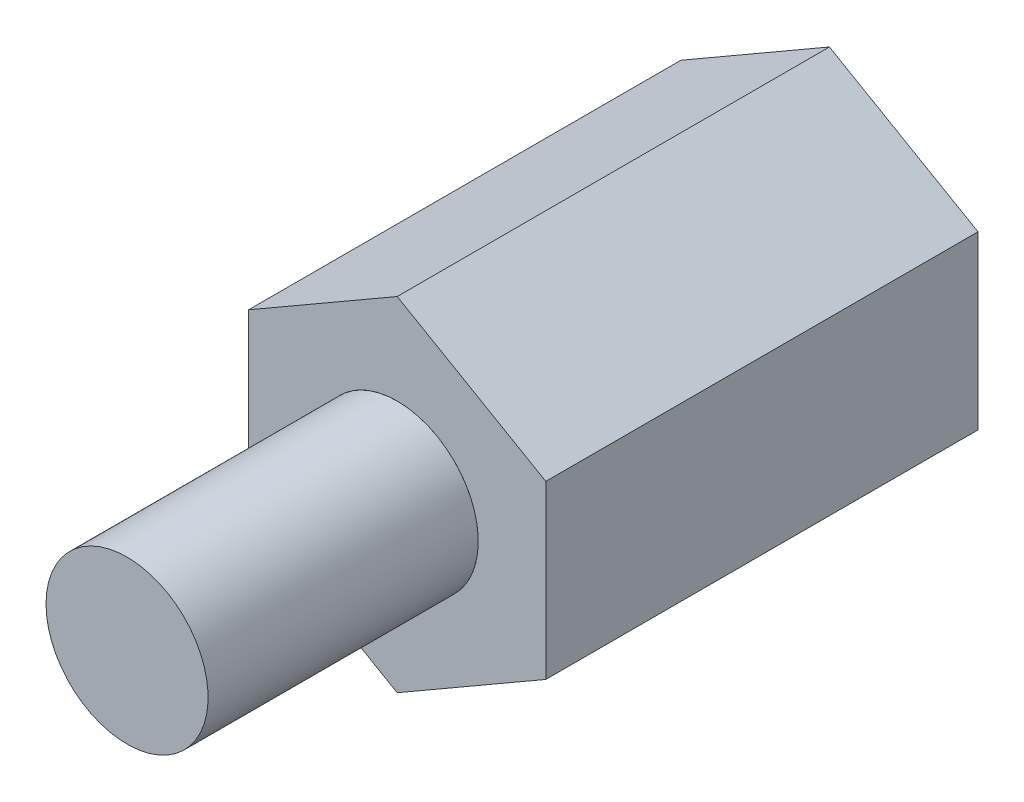
SolidWorks part; units mm, degrees
ref_plane "Спереди" through (0, 0, 0) normal (0, 0, 1) x (1, 0, 0)
ref_plane "Сверху" through (0, 0, 0) normal (0, 1, 0) x (1, 0, 0)
ref_plane "Справа" through (0, 0, 0) normal (1, 0, 0) x (0, 0, -1)
sketch "Эскиз1" plane through (0, 0, 0) normal (0, 0, 1) x (1, 0, 0)
  line L1 (2.75, 1.5877) -> (0, 3.1754)
  line L2 (0, 3.1754) -> (-2.75, 1.5877)
  line L3 (-2.75, 1.5877) -> (-2.75, -1.5877)
  line L4 (-2.75, -1.5877) -> (0, -3.1754)
  line L5 (0, -3.1754) -> (2.75, -1.5877)
  line L6 (2.75, -1.5877) -> (2.75, 1.5877)
  circle A0 centre (0, 0) radius 2.75 construction
  circle A1 centre (0, 0) radius 1.5
  dimension "D2" = 3
  dimension "D1" = 5.5
extrude "Бобышка-Вытянуть1" add sketch "Эскиз1" along normal blind 8
sketch "Эскиз2" plane through (0, 0, 8) normal (0, 0, -1) x (-1, 0, 0)
  circle A0 centre (0, 0) radius 1.5
  circle A1 centre (0, 0) radius 1.5 construction
extrude "Бобышка-Вытянуть2" add sketch "Эскиз2" against normal blind 5 separate body
